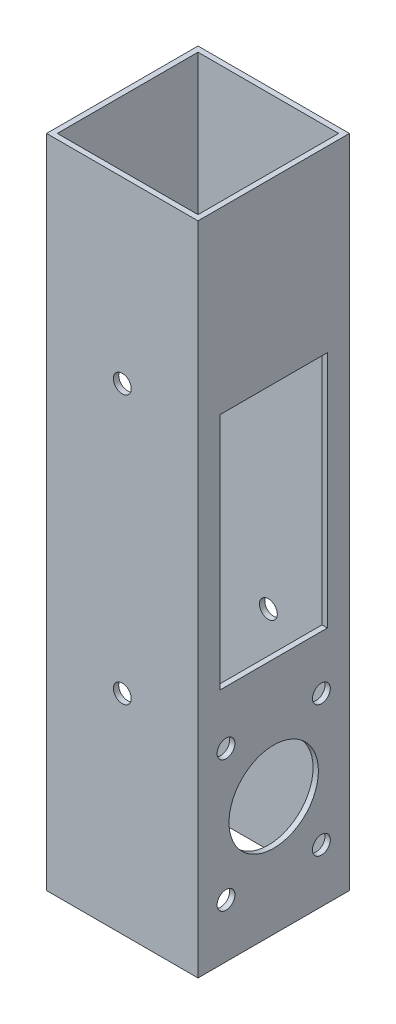
SolidWorks part; units mm, degrees
ref_plane "Front Plane" through (0, 0, 0) normal (0, 0, 1) x (1, 0, 0)
ref_plane "Top Plane" through (0, 0, 0) normal (0, 1, 0) x (1, 0, 0)
ref_plane "Right Plane" through (0, 0, 0) normal (1, 0, 0) x (0, 0, -1)
sketch "Sketch1" plane through (0, 0, 0) normal (0, 1, 0) x (1, 0, 0)
  line L0 (11.8, 11.8) -> (11.8, -11.8)
  line L1 (-12.7, 12.7) -> (12.7, 12.7)
  line L2 (-12.7, 12.7) -> (-12.7, -12.7)
  line L3 (-12.7, -12.7) -> (12.7, -12.7)
  line L4 (12.7, 12.7) -> (12.7, -12.7)
  line L5 (-12.7, 12.7) -> (12.7, -12.7) construction
  line L6 (-12.7, -12.7) -> (12.7, 12.7) construction
  line L7 (-11.8, -11.8) -> (11.8, -11.8)
  line L8 (-11.8, 11.8) -> (-11.8, -11.8)
  line L9 (-11.8, 11.8) -> (11.8, 11.8)
  point P0 (0, 0)
  dimension "D1" = 0.9
extrude "Boss-Extrude1" add sketch "Sketch1" along normal blind 110
sketch "Sketch2" plane through (12.7, 0, 0) normal (1, 0, 0) x (0, 0, -1)
  line L0 (-9, 40) -> (9, 40)
  line L3 (-9, 80) -> (9, 80)
  line L5 (9, 40) -> (9, 80)
  line L6 (-9, 40) -> (-9, 80)
  line L7 (-12.7, 40) -> (12.7, 40) construction
  line L8 (-12.7, 80) -> (12.7, 80) construction
  circle A0 centre (0, 20) radius 7.5
extrude "Cut-Extrude1" cut sketch "Sketch2" against normal blind 25.4
sketch "Sketch3" plane through (0, 0, -12.7) normal (0, 0, -1) x (-1, 0, 0)
  circle A0 centre (0, 35) radius 1.5
  circle A1 centre (0, 80) radius 1.5
extrude "Cut-Extrude2" cut sketch "Sketch3" against normal blind 25.4
sketch "Sketch4" plane through (12.7, 0, 0) normal (1, 0, 0) x (0, 0, -1)
  circle A1 centre (8, 9) radius 1.5
  circle A6 centre (8, 31) radius 1.5
  circle A7 centre (-8, 9) radius 1.5
  circle A8 centre (-8, 31) radius 1.5
extrude "Cut-Extrude3" cut sketch "Sketch4" against normal blind 25.4
